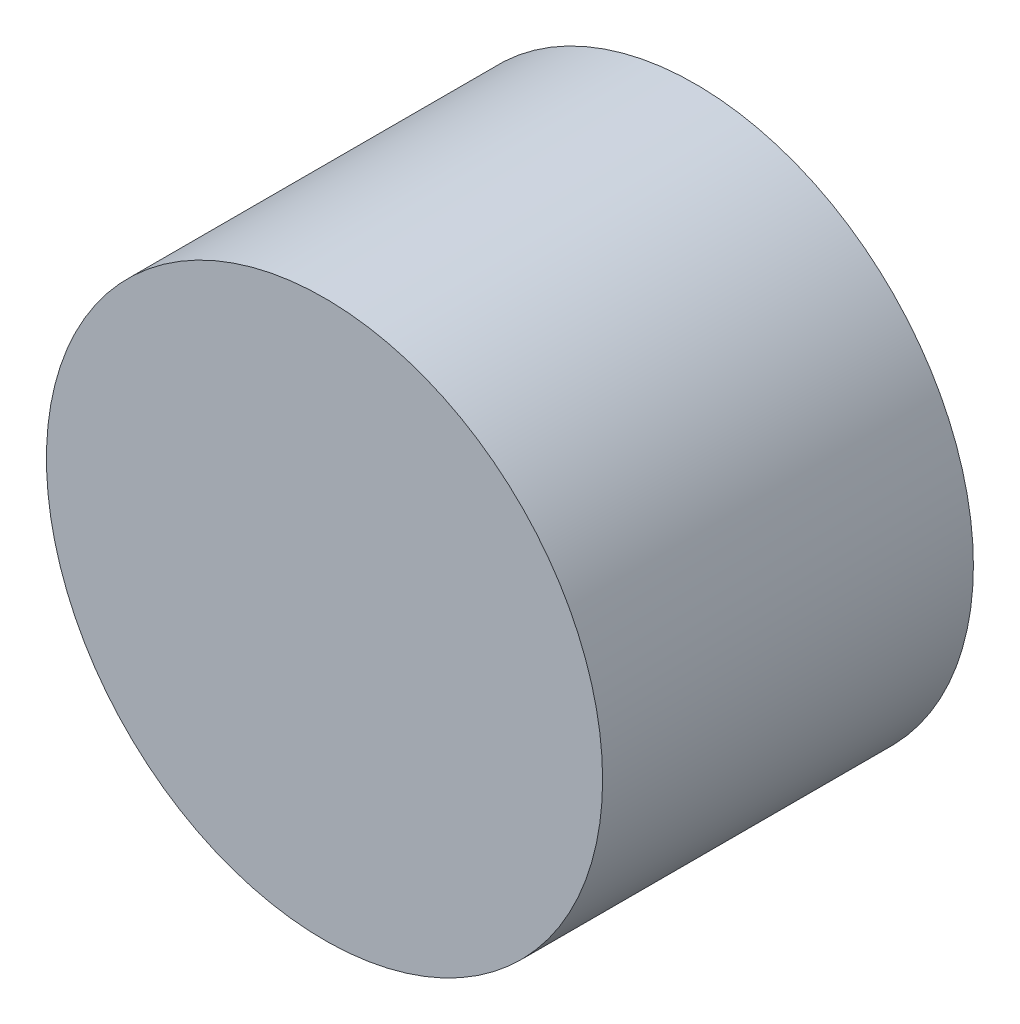
SolidWorks part; units mm, degrees
ref_plane "Front Plane" through (0, 0, 0) normal (0, 0, 1) x (1, 0, 0)
ref_plane "Top Plane" through (0, 0, 0) normal (0, 1, 0) x (1, 0, 0)
ref_plane "Right Plane" through (0, 0, 0) normal (1, 0, 0) x (0, 0, -1)
sketch "Sketch1" plane through (0, 0, 0) normal (0, 0, 1) x (1, 0, 0)
  circle A0 centre (0, 0) radius 38.1
extrude "Boss-Extrude1" add sketch "Sketch1" along normal blind 50.8
